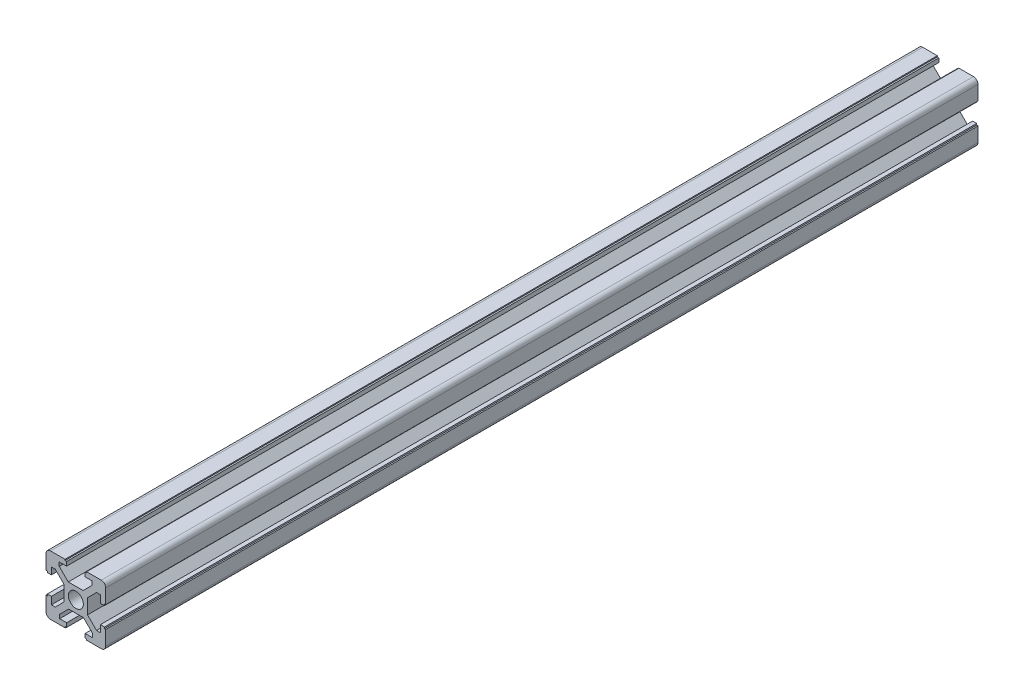
SolidWorks part; units mm, degrees
ref_plane "Front Plane" through (0, 0, 0) normal (0, 0, 1) x (1, 0, 0)
ref_plane "Top Plane" through (0, 0, 0) normal (0, 1, 0) x (1, 0, 0)
ref_plane "Right Plane" through (0, 0, 0) normal (1, 0, 0) x (0, 0, -1)
ref_plane "Plane1" through (0, 0, 0) normal (0, 0, -1) x (-1, 0, 0)
sketch "Sketch1" plane through (0, 0, 0) normal (0, 0, -1) x (-1, 0, 0)
  line L0 (-31.2291, 24.3895) -> (-31.2291, 19.5741)
  line L1 (-31.2291, 19.5741) -> (-30.8015, 19.5741)
  line L2 (-30.8015, 19.5741) -> (-30.8015, 19.0554)
  line L3 (-30.8015, 19.0554) -> (-29.4291, 19.0554)
  line L4 (-29.4291, 19.0554) -> (-29.4291, 21.5235)
  line L5 (-29.4291, 21.5235) -> (-28.1416, 21.5235)
  line L6 (-28.1416, 21.5235) -> (-25.1291, 18.511)
  line L7 (-25.1291, 18.511) -> (-25.1291, 13.533)
  line L8 (-25.1291, 13.533) -> (-28.1416, 10.5205)
  line L9 (-28.1416, 10.5205) -> (-29.4291, 10.5205)
  line L10 (-29.4291, 10.5205) -> (-29.4291, 12.8554)
  line L11 (-29.4291, 12.8554) -> (-30.8015, 12.8554)
  line L12 (-30.8015, 12.8554) -> (-30.8015, 12.3507)
  line L13 (-30.8015, 12.3507) -> (-31.2291, 12.3507)
  line L14 (-31.2291, 12.3507) -> (-31.2291, 7.5212)
  line L15 (-29.7291, 6.0212) -> (-24.8478, 6.0212)
  line L16 (-24.8478, 6.0212) -> (-24.8478, 6.383)
  line L17 (-24.8478, 6.383) -> (-24.3291, 6.383)
  line L18 (-24.3291, 6.383) -> (-24.3291, 7.7554)
  line L19 (-24.3291, 7.7554) -> (-26.7973, 7.7554)
  line L20 (-26.7973, 7.7554) -> (-26.7973, 9.0429)
  line L21 (-26.7973, 9.0429) -> (-23.7848, 12.0554)
  line L22 (-23.7848, 12.0554) -> (-18.8067, 12.0554)
  line L23 (-18.8067, 12.0554) -> (-15.7942, 9.0429)
  line L24 (-15.7942, 9.0429) -> (-15.7942, 7.7554)
  line L25 (-15.7942, 7.7554) -> (-18.1291, 7.7554)
  line L26 (-18.1291, 7.7554) -> (-18.1291, 6.383)
  line L27 (-18.1291, 6.383) -> (-17.6244, 6.383)
  line L28 (-17.6244, 6.383) -> (-17.6244, 6.0212)
  line L29 (-17.6244, 6.0212) -> (-12.7291, 6.0212)
  line L30 (-11.2291, 7.5212) -> (-11.2291, 12.3367)
  line L31 (-11.2291, 12.3367) -> (-11.6567, 12.3367)
  line L32 (-11.6567, 12.3367) -> (-11.6567, 12.8554)
  line L33 (-11.6567, 12.8554) -> (-13.0291, 12.8554)
  line L34 (-13.0291, 12.8554) -> (-13.0291, 10.3872)
  line L35 (-13.0291, 10.3872) -> (-14.3166, 10.3872)
  line L36 (-14.3166, 10.3872) -> (-17.3291, 13.3997)
  line L37 (-17.3291, 13.3997) -> (-17.3291, 18.3778)
  line L38 (-17.3291, 18.3778) -> (-14.3166, 21.3903)
  line L39 (-14.3166, 21.3903) -> (-13.0291, 21.3903)
  line L40 (-13.0291, 21.3903) -> (-13.0291, 19.0554)
  line L41 (-13.0291, 19.0554) -> (-11.6567, 19.0554)
  line L42 (-11.6567, 19.0554) -> (-11.6567, 19.56)
  line L43 (-11.6567, 19.56) -> (-11.2291, 19.56)
  line L44 (-11.2291, 19.56) -> (-11.2291, 24.3895)
  line L45 (-12.7291, 25.8895) -> (-17.6104, 25.8895)
  line L46 (-17.6104, 25.8895) -> (-17.6104, 25.5277)
  line L47 (-17.6104, 25.5277) -> (-18.1291, 25.5277)
  line L48 (-18.1291, 25.5277) -> (-18.1291, 24.1554)
  line L49 (-18.1291, 24.1554) -> (-15.661, 24.1554)
  line L50 (-15.661, 24.1554) -> (-15.661, 22.8679)
  line L51 (-15.661, 22.8679) -> (-18.6734, 19.8554)
  line L52 (-18.6734, 19.8554) -> (-23.6515, 19.8554)
  line L53 (-23.6515, 19.8554) -> (-26.664, 22.8679)
  line L54 (-26.664, 22.8679) -> (-26.664, 24.1554)
  line L55 (-26.664, 24.1554) -> (-24.3291, 24.1554)
  line L56 (-24.3291, 24.1554) -> (-24.3291, 25.5277)
  line L57 (-24.3291, 25.5277) -> (-24.8338, 25.5277)
  line L58 (-24.8338, 25.5277) -> (-24.8338, 25.8895)
  line L59 (-24.8338, 25.8895) -> (-29.7291, 25.8895)
  circle A0 centre (-21.2291, 15.9554) radius 2.5
  arc A1 (-31.2291, 7.5212) -> (-29.7291, 6.0212) centre (-29.7291, 7.5212) ccw
  arc A2 (-12.7291, 6.0212) -> (-11.2291, 7.5212) centre (-12.7291, 7.5212) ccw
  arc A3 (-11.2291, 24.3895) -> (-12.7291, 25.8895) centre (-12.7291, 24.3895) ccw
  arc A4 (-29.7291, 25.8895) -> (-31.2291, 24.3895) centre (-29.7291, 24.3895) ccw
extrude "Boss-Extrude1" add sketch "Sketch1" against normal blind 292
